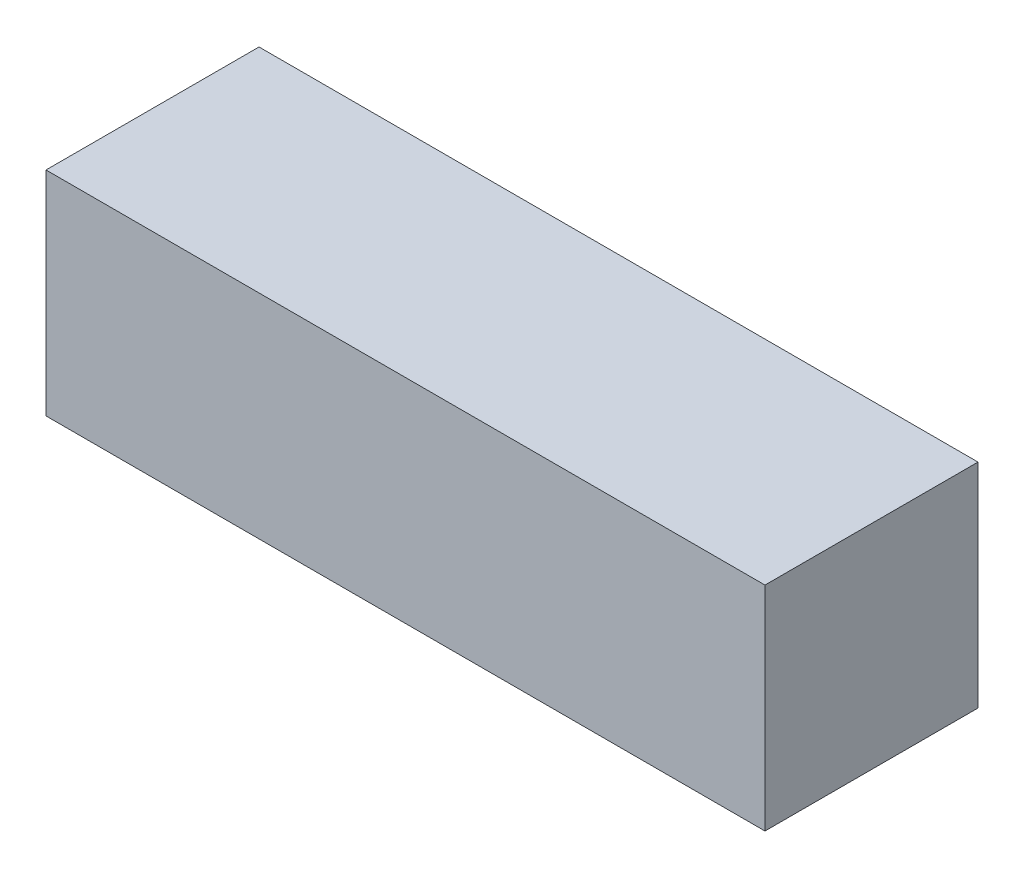
SolidWorks part; units mm, degrees
material "Low Carbon Steel"
ref_plane "Front Plane" through (0, 0, 0) normal (0, 0, 1) x (1, 0, 0)
ref_plane "Top Plane" through (0, 0, 0) normal (0, 1, 0) x (1, 0, 0)
ref_plane "Right Plane" through (0, 0, 0) normal (1, 0, 0) x (0, 0, -1)
sketch "Sketch1" plane through (0, 0, 0) normal (0, 0, 1) x (1, 0, 0)
  line L0 (85.725, 25.4) -> (-85.725, -25.4) construction
  line L1 (-85.725, 25.4) -> (85.725, 25.4)
  line L2 (-85.725, 25.4) -> (-85.725, -25.4)
  line L3 (-85.725, -25.4) -> (85.725, -25.4)
  line L4 (85.725, 25.4) -> (85.725, -25.4)
  dimension "D1" = 50.8
  dimension "D2" = 171.45
extrude "Boss-Extrude1" add sketch "Sketch1" along normal blind 50.8
other "Freeze***"
